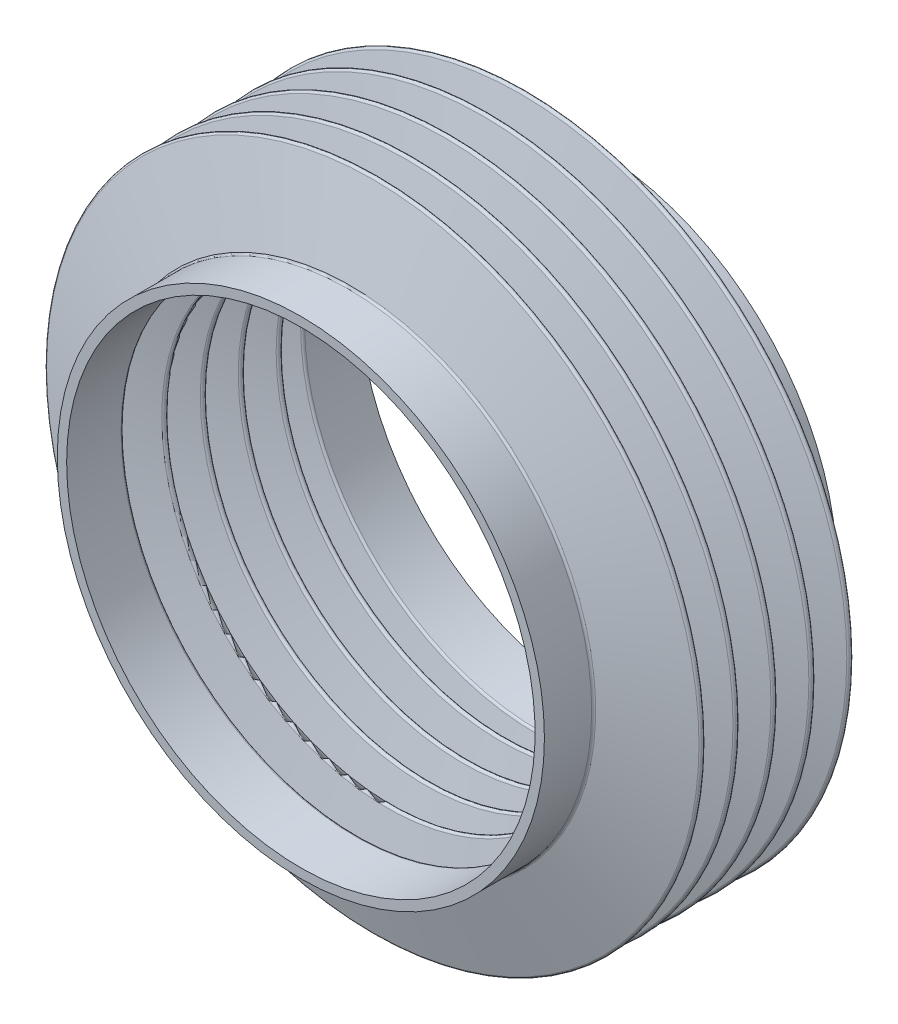
SolidWorks part; units mm, degrees
ref_plane "Front Plane" through (0, 0, 0) normal (0, 0, 1) x (1, 0, 0)
ref_plane "Top Plane" through (0, 0, 0) normal (0, 1, 0) x (1, 0, 0)
ref_plane "Right Plane" through (0, 0, 0) normal (1, 0, 0) x (0, 0, -1)
sketch "Sketch1" plane through (0, 0, 0) normal (0, 1, 0) x (1, 0, 0)
  line L0 (0, 81.4371) -> (0, -40.8048) construction
  line L1 (-47.5439, 0) -> (71.2417, 0) construction
  line L2 (-25, 31.21) -> (-25, 25.4086)
  line L3 (-25, 0) -> (-25, 5.8098)
  line L4 (-23, 46.2593) -> (-23, -4.1974) construction
  line L5 (-29.3489, 28.21) -> (7.1339, 28.21) construction
  line L6 (-25.1833, 6.0507) -> (-30.4829, 7.5173)
  line L7 (-25.1935, 25.1651) -> (-30.4774, 23.9394)
  line L8 (-30.4802, 23.453) -> (-24.0198, 21.8745)
  line L9 (-24.0226, 21.3881) -> (-30.4774, 19.8908)
  line L10 (-30.4802, 19.4044) -> (-24.0198, 17.8259)
  line L11 (-24.0226, 17.3395) -> (-30.4774, 15.8422)
  line L12 (-30.4802, 15.3558) -> (-24.0198, 13.7773)
  line L13 (-24.0226, 13.2909) -> (-30.4774, 11.7936)
  line L14 (-30.4802, 11.3072) -> (-24.0993, 9.7481)
  line L15 (-24.1101, 9.26) -> (-30.4647, 8.0035)
  line L16 (-26, 31.21) -> (-26, 26.2032)
  line L17 (-26.1935, 25.9597) -> (-34.7939, 23.9647)
  line L18 (-34.7967, 23.4783) -> (-28.3363, 21.8998)
  line L19 (-28.3391, 21.4134) -> (-34.7939, 19.9161)
  line L20 (-34.7967, 19.4297) -> (-28.3363, 17.8512)
  line L21 (-28.3391, 17.3648) -> (-34.7939, 15.8675)
  line L22 (-34.7967, 15.3811) -> (-28.3363, 13.8026)
  line L23 (-28.3391, 13.3162) -> (-34.7939, 11.8189)
  line L24 (-34.7967, 11.3325) -> (-28.7338, 9.8511)
  line L25 (-28.7447, 9.363) -> (-34.7999, 8.1657)
  line L26 (-26.1833, 5.2899) -> (-34.8181, 7.6795)
  line L27 (-26, 0) -> (-26, 5.0489)
  line L28 (-31.5, 23.7022) -> (-23, 21.6253) construction
  line L29 (-25, 25.21) -> (-31.5, 23.7022) construction
  line L30 (-35.8165, 23.7274) -> (-27.3165, 21.6506) construction
  line L31 (-26, 26.0046) -> (-35.8165, 23.7274) construction
  line L32 (-25, 31.21) -> (-25, 25.21) construction
  line L33 (-26, 31.21) -> (-26, 26.0046) construction
  line L34 (-26, 0) -> (-26, 5.2392) construction
  line L35 (-26, 5.2392) -> (-35.8352, 7.961) construction
  line L36 (-25, 0) -> (-25, 6) construction
  line L37 (-25, 6) -> (-31.5, 7.7988) construction
  line L38 (-23, 9.4796) -> (-31.5, 7.7988) construction
  line L39 (-27.6345, 9.5825) -> (-35.8352, 7.961) construction
  line L40 (-35.8165, 11.5817) -> (-27.6345, 9.5825) construction
  line L41 (-31.5, 11.5564) -> (-23, 9.4796) construction
  line L42 (-23, 13.5281) -> (-31.5, 11.5564) construction
  line L43 (-27.3165, 13.5534) -> (-35.8165, 11.5817) construction
  line L44 (-35.8165, 15.6303) -> (-27.3165, 13.5534) construction
  line L45 (-31.5, 15.605) -> (-23, 13.5281) construction
  line L46 (-23, 17.5767) -> (-31.5, 15.605) construction
  line L47 (-27.3165, 17.602) -> (-35.8165, 15.6303) construction
  line L48 (-35.8165, 19.6789) -> (-27.3165, 17.602) construction
  line L49 (-31.5, 19.6536) -> (-23, 17.5767) construction
  line L50 (-23, 21.6253) -> (-31.5, 19.6536) construction
  line L51 (-27.3165, 21.6506) -> (-35.8165, 19.6789) construction
  line L52 (-26, 31.21) -> (-25, 31.21)
  line L53 (-26, 0) -> (-25, 0)
  arc A0 (-30.4802, 23.453) -> (-30.4774, 23.9394) centre (-30.4209, 23.6959) cw
  arc A1 (-34.7967, 23.4783) -> (-34.7939, 23.9647) centre (-34.7374, 23.7211) cw
  arc A2 (-25.1935, 25.1651) -> (-25, 25.4086) centre (-25.25, 25.4086) ccw
  arc A3 (-26.1935, 25.9597) -> (-26, 26.2032) centre (-26.25, 26.2032) ccw
  arc A4 (-26, 5.0489) -> (-26.1833, 5.2899) centre (-26.25, 5.0489) ccw
  arc A5 (-25, 5.8098) -> (-25.1833, 6.0507) centre (-25.25, 5.8098) ccw
  arc A6 (-30.4829, 7.5173) -> (-30.4647, 8.0035) centre (-30.4162, 7.7583) cw
  arc A7 (-34.8181, 7.6795) -> (-34.7999, 8.1657) centre (-34.7514, 7.9204) cw
  arc A8 (-28.7447, 9.363) -> (-28.7338, 9.8511) centre (-28.7932, 9.6083) ccw
  arc A9 (-24.1101, 9.26) -> (-24.0993, 9.7481) centre (-24.1586, 9.5053) ccw
  arc A10 (-30.4802, 11.3072) -> (-30.4774, 11.7936) centre (-30.4209, 11.5501) cw
  arc A11 (-34.7967, 11.3325) -> (-34.7939, 11.8189) centre (-34.7374, 11.5753) cw
  arc A12 (-28.3391, 13.3162) -> (-28.3363, 13.8026) centre (-28.3956, 13.5597) ccw
  arc A13 (-24.0226, 13.2909) -> (-24.0198, 13.7773) centre (-24.0791, 13.5345) ccw
  arc A14 (-30.4802, 15.3558) -> (-30.4774, 15.8422) centre (-30.4209, 15.5987) cw
  arc A15 (-34.7967, 15.3811) -> (-34.7939, 15.8675) centre (-34.7374, 15.6239) cw
  arc A16 (-28.3391, 17.3648) -> (-28.3363, 17.8512) centre (-28.3956, 17.6083) ccw
  arc A17 (-24.0226, 17.3395) -> (-24.0198, 17.8259) centre (-24.0791, 17.5831) ccw
  arc A18 (-30.4802, 19.4044) -> (-30.4774, 19.8908) centre (-30.4209, 19.6473) cw
  arc A19 (-34.7967, 19.4297) -> (-34.7939, 19.9161) centre (-34.7374, 19.6725) cw
  arc A20 (-28.3391, 21.4134) -> (-28.3363, 21.8998) centre (-28.3956, 21.6569) ccw
  arc A21 (-24.0226, 21.3881) -> (-24.0198, 21.8745) centre (-24.0791, 21.6317) ccw
  point P38 (-31.5, 23.7022)
  dimension "D13" = 0.25
  dimension "D14" = 0.25
  dimension "D2" = 25
  dimension "D3" = 31.21
  dimension "D5" = 23
  dimension "D7" = 31.5
  dimension "D12" = 1
revolve "Revolve1" add sketch "Sketch1" angle 360 about L0
